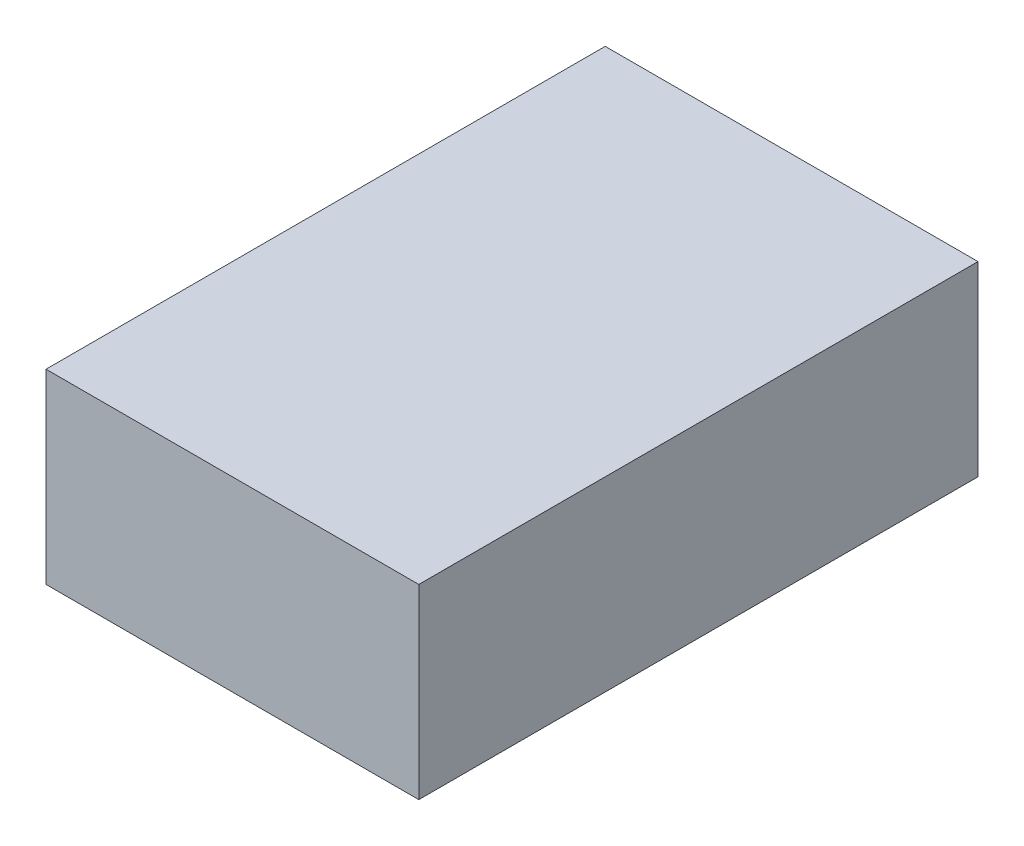
SolidWorks part; units mm, degrees
ref_plane "前视基准面" through (0, 0, 0) normal (0, 0, 1) x (1, 0, 0)
ref_plane "上视基准面" through (0, 0, 0) normal (0, 1, 0) x (1, 0, 0)
ref_plane "右视基准面" through (0, 0, 0) normal (1, 0, 0) x (0, 0, -1)
sketch "草图1" plane through (0, 0, 0) normal (0, 1, 0) x (1, 0, 0)
  line L1 (-16.158, 10.8259) -> (3.842, 10.8259)
  line L2 (-16.158, 10.8259) -> (-16.158, -19.1741)
  line L3 (-16.158, -19.1741) -> (3.842, -19.1741)
  line L4 (3.842, 10.8259) -> (3.842, -19.1741)
  dimension "D1" = 20
  dimension "D2" = 30
extrude "凸台-拉伸1" add sketch "草图1" along normal blind 10
